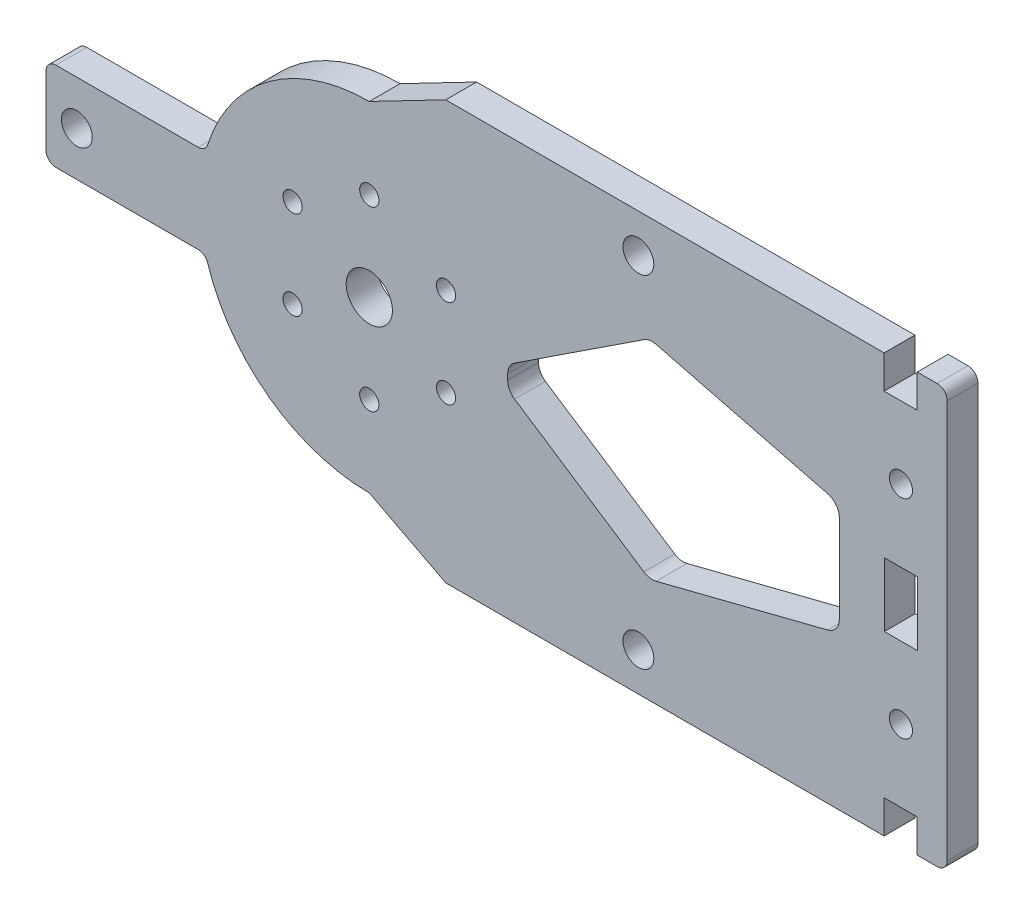
SolidWorks part; units mm, degrees
ref_plane "前视基准面" through (0, 0, 0) normal (0, 0, 1) x (1, 0, 0)
ref_plane "上视基准面" through (0, 0, 0) normal (0, 1, 0) x (1, 0, 0)
ref_plane "右视基准面" through (0, 0, 0) normal (1, 0, 0) x (0, 0, -1)
sketch "草图1" plane through (0, 0, 0) normal (0, 0, 1) x (1, 0, 0)
  line L0 (30.001, 15) -> (30.001, 12) construction
  line L1 (27.8157, 27.15) -> (32.1157, 27.15) construction
  line L2 (32.151, -4.15) -> (27.851, -4.15)
  line L3 (32.151, -4.15) -> (32.151, 4.15)
  line L4 (32.151, 4.15) -> (27.851, 4.15)
  line L5 (27.851, -4.15) -> (27.851, 4.15)
  line L6 (32.151, -4.15) -> (27.851, 4.15) construction
  line L7 (32.151, 4.15) -> (27.851, -4.15) construction
  line L8 (32.1157, 27.15) -> (32.1157, 22.85)
  line L9 (27.8157, 22.85) -> (32.1157, 22.85)
  line L10 (27.8157, 27.15) -> (27.8157, 22.85)
  line L11 (30.001, 0) -> (30.8707, 0) construction
  line L12 (27.8157, -27.15) -> (32.1157, -27.15) construction
  line L13 (30.001, -15) -> (30.001, -12) construction
  line L14 (27.8157, -27.15) -> (27.8157, -22.85)
  line L15 (27.8157, -22.85) -> (32.1157, -22.85)
  line L16 (32.1157, -27.15) -> (32.1157, -22.85)
  line L17 (32.1157, -27.15) -> (36.001, -27.15)
  line L18 (36.001, -27.15) -> (36.001, 27.15)
  line L19 (36.001, 27.15) -> (32.1157, 27.15)
  line L23 (-38.999, -22.002) -> (-29.075, -27.15)
  line L25 (-38.999, 22.002) -> (-29.075, 27.15)
  line L29 (27.8157, -27.15) -> (-29.075, -27.15)
  line L30 (-29.075, 27.15) -> (27.8157, 27.15)
  line L31 (-29.075, -27.15) -> (-29.075, 27.15) construction
  line L34 (-48.9583, 5.75) -> (-48.9583, -5.75) construction
  line L38 (-60.2364, 5.75) -> (-80.9583, 5.75)
  line L39 (-80.9583, -5.75) -> (-60.2364, -5.75)
  line L40 (-80.9583, 5.75) -> (-80.9583, -5.75)
  line L41 (30.001, -13.5) -> (30.001, 13.5) construction
  line L42 (30.001, 13.5) -> (-4.075, 22.15) construction
  line L43 (-4.075, 22.15) -> (-29.0397, 5.75) construction
  line L44 (-29.0397, 5.75) -> (-29.0397, -5.75) construction
  line L45 (-29.0397, -5.75) -> (-4.075, -22.15) construction
  line L46 (-4.075, -22.15) -> (30.001, -13.5) construction
  line L47 (-2.6278, -13.5289) -> (22.001, -7.277)
  line L48 (22.001, -7.277) -> (22.001, 7.277)
  line L49 (22.001, 7.277) -> (-2.6278, 13.5289)
  line L50 (-2.6278, 13.5289) -> (-21.0397, 1.4336)
  line L51 (-21.0397, 1.4336) -> (-21.0397, -1.4336)
  line L52 (-21.0397, -1.4336) -> (-2.6278, -13.5289)
  circle A0 centre (30.001, 13.5) radius 1.5
  circle A1 centre (30.001, -13.5) radius 1.5
  circle A3 centre (-38.999, 0) radius 3
  circle A6 centre (-38.999, 0) radius 11.5 construction
  circle A7 centre (-38.999, -11.5) radius 1.25
  circle A18 centre (-38.999, 0) radius 22.002 construction
  circle A25 centre (-48.9583, -5.75) radius 1.25
  circle A26 centre (-48.9583, 5.75) radius 1.25
  circle A27 centre (-38.999, 11.5) radius 1.25
  circle A28 centre (-29.0397, 5.75) radius 1.25
  circle A29 centre (-29.0397, -5.75) radius 1.25
  circle A30 centre (-4.075, -22.15) radius 2
  circle A31 centre (-4.075, 22.15) radius 2
  arc A32 (-38.999, -22.002) -> (-60.2364, -5.75) centre (-38.999, 0) cw
  arc A33 (-60.2364, 5.75) -> (-38.999, 22.002) centre (-38.999, 0) cw
  circle A34 centre (-76.9583, 0) radius 2
  point P4 (30.001, 0)
  dimension "D3" = 6
  dimension "D4" = 75
  dimension "D5" = 6
  dimension "D6" = 11.5
  dimension "D7" = 23
  dimension "D8" = 2.5
  dimension "D9" = 25
  dimension "D11" = 5
  dimension "D14" = 4
  dimension "D1" = 8.3
  dimension "D2" = 4.3
  dimension "D10" = 5
  dimension "D12" = 25
  dimension "D13" = 28
  dimension "D15" = 3.8853
  dimension "D16" = 4.3
  dimension "D17" = 8
extrude "凸台-拉伸1" add sketch "草图1" along normal blind 4
fillet "圆角1" radius 1.3 6 edges at (36.001, -27.15, 2) (36.001, 27.15, 2) (-80.9583, -5.75, 2) (-80.9583, 5.75, 2) (-60.2364, 5.75, 2) (-60.2364, -5.75, 2)
fillet "圆角2" radius 2 6 edges at (22.001, 7.277, 2) (22.001, -7.277, 2) (-2.6278, -13.5289, 2) (-2.6278, 13.5289, 2) (-21.0397, 1.4336, 2) (-21.0397, -1.4336, 2)
